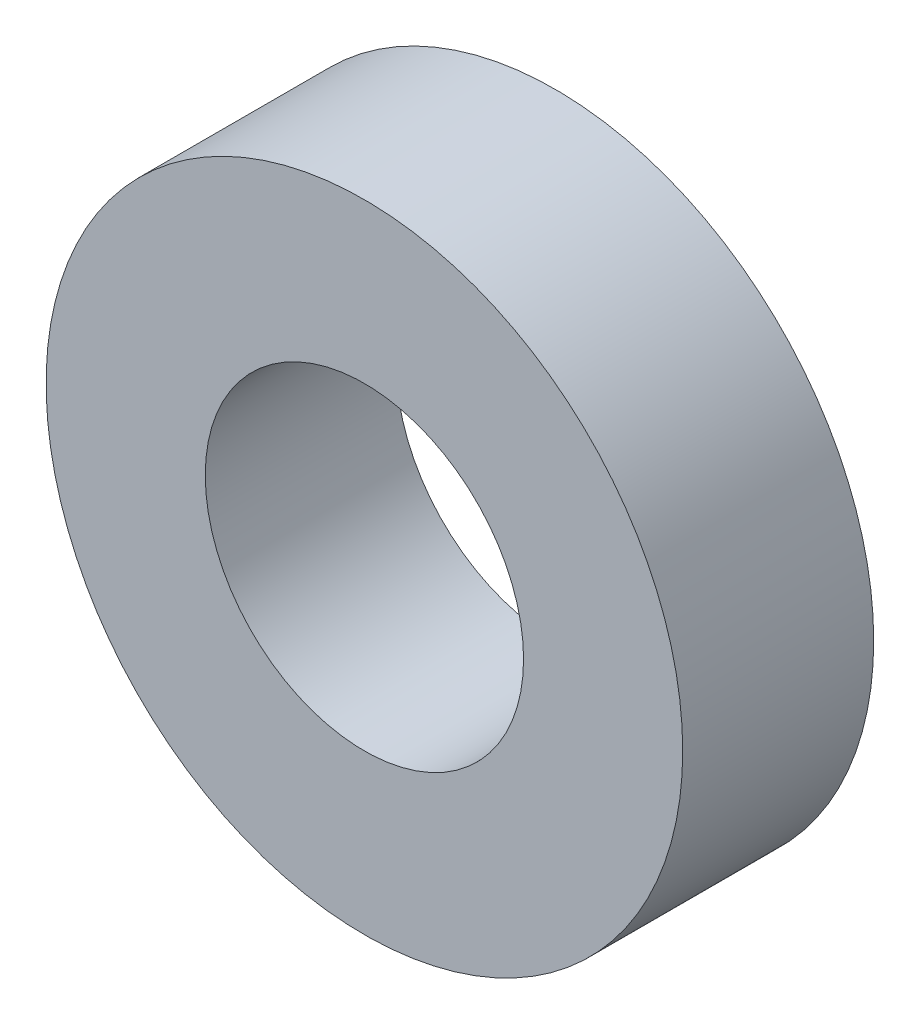
SolidWorks part; units mm, degrees
ref_plane "Plano frontal" through (0, 0, 0) normal (0, 0, 1) x (1, 0, 0)
ref_plane "Plano superior" through (0, 0, 0) normal (0, 1, 0) x (1, 0, 0)
ref_plane "Plano direito" through (0, 0, 0) normal (1, 0, 0) x (0, 0, -1)
sketch "Esboço1" plane through (0, 0, 0) normal (0, 0, 1) x (1, 0, 0)
  circle A0 centre (-23, 23) radius 5 construction
  circle A1 centre (-23, 23) radius 5
  circle A2 centre (-23, 23) radius 2.5
  dimension "D1" = 5
extrude "Ressalto-extrusão1" add sketch "Esboço1" along normal blind 3
